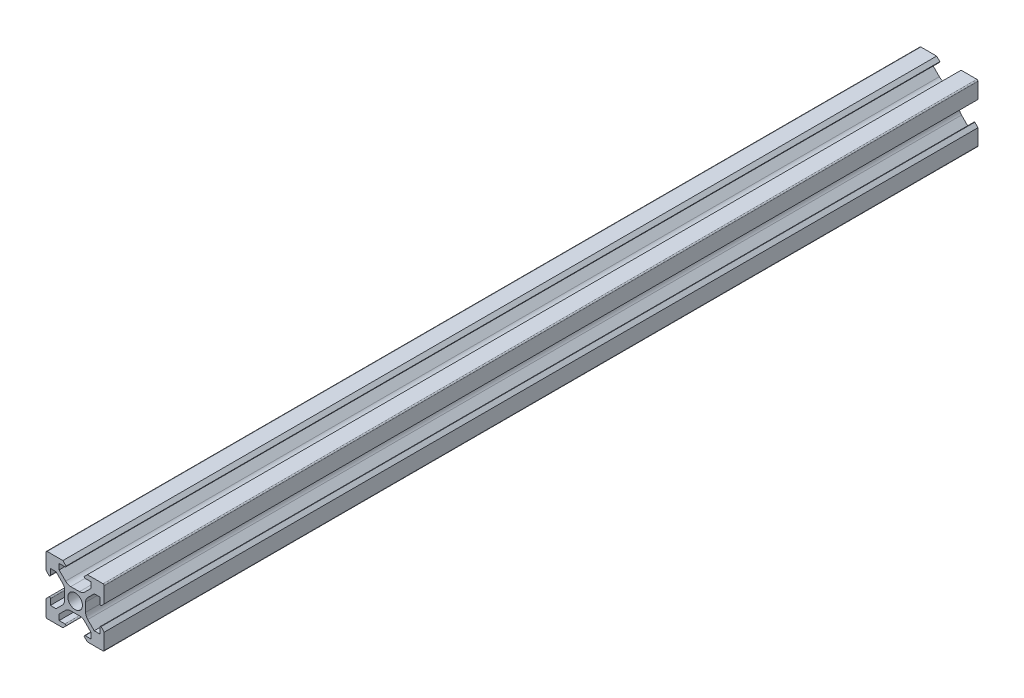
SolidWorks part; units mm, degrees
ref_plane "Plano frontal" through (0, 0, 0) normal (0, 0, 1) x (1, 0, 0)
ref_plane "Plano superior" through (0, 0, 0) normal (0, 1, 0) x (1, 0, 0)
ref_plane "Plano direito" through (0, 0, 0) normal (1, 0, 0) x (0, 0, -1)
sketch "Esboço1" plane through (0, 0, 0) normal (0, 0, 1) x (1, 0, 0)
  line L0 (-3.1, 8.9) -> (-4.2, 10)
  line L1 (-9.6, 10) -> (-4.2, 10)
  line L2 (-3.6, 1.5038) -> (-3.6, 0)
  line L3 (-8.5, 5.5) -> (-8.5, 3.5)
  line L4 (-6.5607, 5.5) -> (-4.3322, 3.2716)
  line L5 (-8.5, 5.5) -> (-6.5607, 5.5)
  line L6 (-10, 9.6) -> (-10, 4.2)
  line L7 (-8.9, 3.1) -> (-10, 4.2)
  line L8 (0, 3.6) -> (0, -3.6) construction
  line L9 (9.8828, -9.8828) -> (0, 0) construction
  line L10 (9.8828, 9.8828) -> (0, 0) construction
  line L11 (3.6, -1.5038) -> (3.6, 0)
  line L12 (8.5, -5.5) -> (8.5, -3.5)
  line L13 (-5.5, 8.5) -> (-5.5, 6.5607)
  line L14 (6.5607, -5.5) -> (4.3322, -3.2716)
  line L15 (8.5, -5.5) -> (6.5607, -5.5)
  line L16 (3.1, -8.9) -> (4.2, -10)
  line L17 (9.6, -10) -> (4.2, -10)
  line L18 (5.5, -8.5) -> (5.5, -6.5607)
  line L19 (-18.5, 8.5) -> (-18.5, -8.5) construction
  line L20 (5.5, -6.5607) -> (3.2716, -4.3322)
  line L21 (5.5, -8.5) -> (3.5, -8.5)
  line L22 (10, -9.6) -> (10, -4.2)
  line L23 (-9.8828, 9.8828) -> (0, 0) construction
  line L24 (8.9, -3.1) -> (10, -4.2)
  line L25 (-5.5, 6.5607) -> (-3.2716, 4.3322)
  line L26 (5.5, 8.5) -> (3.5, 8.5)
  line L27 (-20, 10) -> (-20, -10) construction
  line L28 (5.5, 6.5607) -> (3.2716, 4.3322)
  line L29 (5.5, 8.5) -> (5.5, 6.5607)
  line L30 (8.9, 3.1) -> (10, 4.2)
  line L31 (10, 9.6) -> (10, 4.2)
  line L32 (8.5, 5.5) -> (6.5607, 5.5)
  line L33 (-5.5, 8.5) -> (-3.5, 8.5)
  line L34 (6.5607, 5.5) -> (4.3322, 3.2716)
  line L35 (8.5, 5.5) -> (8.5, 3.5)
  line L36 (-20, 10) -> (0, 10) construction
  line L37 (3.6, 1.5038) -> (3.6, 0)
  line L38 (9.6, 10) -> (4.2, 10)
  line L39 (-18.5, 8.5) -> (-1.5, 8.5) construction
  line L40 (-1.5038, 3.6) -> (1.5038, 3.6)
  line L41 (3.1, 8.9) -> (4.2, 10)
  line L42 (-8.9, -3.1) -> (-10, -4.2)
  line L43 (-10, -9.6) -> (-10, -4.2)
  line L44 (-1.5038, -3.6) -> (1.5038, -3.6)
  line L45 (-5.5, -8.5) -> (-3.5, -8.5)
  line L46 (-5.5, -6.5607) -> (-3.2716, -4.3322)
  line L47 (-5.5, -8.5) -> (-5.5, -6.5607)
  line L48 (-9.6, -10) -> (-4.2, -10)
  line L49 (-3.1, -8.9) -> (-4.2, -10)
  line L50 (-8.5, -5.5) -> (-6.5607, -5.5)
  line L51 (-6.5607, -5.5) -> (-4.3322, -3.2716)
  line L52 (-8.5, -5.5) -> (-8.5, -3.5)
  line L53 (-3.6, -1.5038) -> (-3.6, 0)
  line L54 (0, 10) -> (0, -10) construction
  line L55 (-20, -10) -> (0, -10) construction
  line L56 (-9.8828, -9.8828) -> (0, 0) construction
  line L57 (-18.5, -8.5) -> (-1.5, -8.5) construction
  line L58 (-1.5, 8.5) -> (-1.5, -8.5) construction
  arc A0 (2.5, 0) -> (-2.5, 0) centre (0, 0) ccw
  arc A1 (-3.5, 8.5) -> (-3.1, 8.9) centre (-3.5, 8.9) ccw
  arc A2 (-9.6, 10) -> (-10, 9.6) centre (-9.6, 9.6) ccw
  arc A3 (-3.2716, 4.3322) -> (-1.5038, 3.6) centre (-1.5038, 6.1) ccw
  arc A4 (-4.3322, 3.2716) -> (-3.6, 1.5038) centre (-6.1, 1.5038) cw
  arc A5 (-8.5, 3.5) -> (-8.9, 3.1) centre (-8.9, 3.5) cw
  arc A6 (3.5, -8.5) -> (3.1, -8.9) centre (3.5, -8.9) ccw
  arc A7 (3.2716, -4.3322) -> (1.5038, -3.6) centre (1.5038, -6.1) ccw
  arc A8 (4.3322, -3.2716) -> (3.6, -1.5038) centre (6.1, -1.5038) cw
  arc A9 (10, -9.6) -> (9.6, -10) centre (9.6, -9.6) cw
  arc A10 (8.5, -3.5) -> (8.9, -3.1) centre (8.9, -3.5) cw
  arc A11 (8.5, 3.5) -> (8.9, 3.1) centre (8.9, 3.5) ccw
  arc A12 (4.3322, 3.2716) -> (3.6, 1.5038) centre (6.1, 1.5038) ccw
  arc A13 (3.2716, 4.3322) -> (1.5038, 3.6) centre (1.5038, 6.1) cw
  arc A14 (9.6, 10) -> (10, 9.6) centre (9.6, 9.6) cw
  arc A15 (3.5, 8.5) -> (3.1, 8.9) centre (3.5, 8.9) cw
  arc A16 (-2.5, 0) -> (2.5, 0) centre (0, 0) ccw
  arc A17 (-8.5, -3.5) -> (-8.9, -3.1) centre (-8.9, -3.5) ccw
  arc A18 (-10, -9.6) -> (-9.6, -10) centre (-9.6, -9.6) ccw
  arc A19 (-4.3322, -3.2716) -> (-3.6, -1.5038) centre (-6.1, -1.5038) ccw
  arc A20 (-3.2716, -4.3322) -> (-1.5038, -3.6) centre (-1.5038, -6.1) cw
  arc A21 (-3.5, -8.5) -> (-3.1, -8.9) centre (-3.5, -8.9) cw
  point P103 (0, 0)
  dimension "D1" = 45
  dimension "D3" = 20
  dimension "D2" = 0.4
extrude "Ressalto-extrusão1" add sketch "Esboço1" along normal mid plane 300
